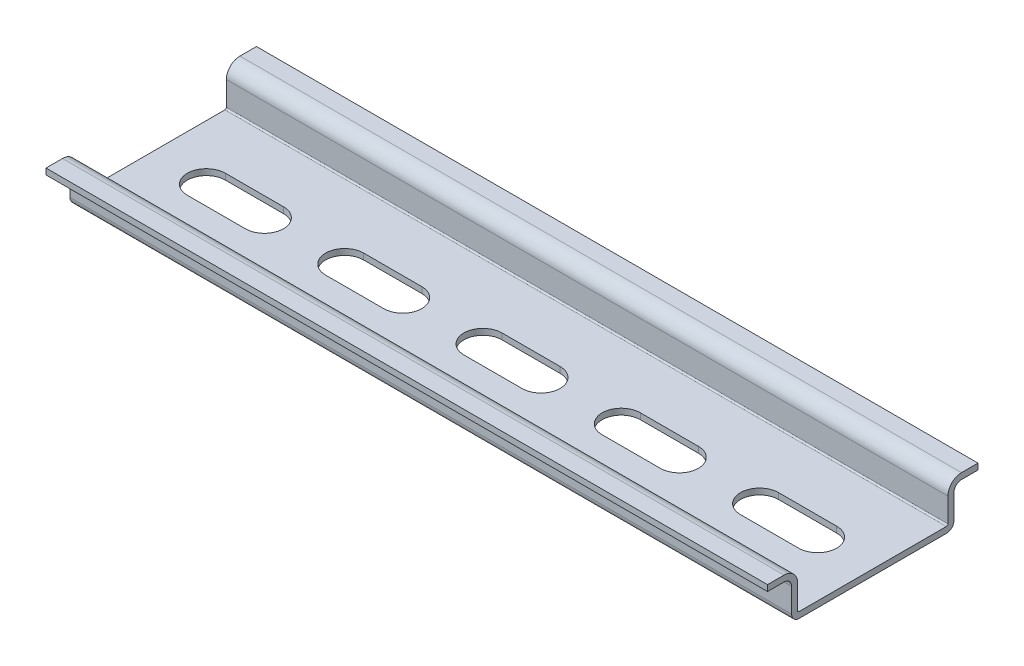
SolidWorks part; units mm, degrees
material "Stainless Steel (ferritic)"
ref_plane "Front Plane" through (0, 0, 0) normal (0, 0, 1) x (1, 0, 0)
ref_plane "Top Plane" through (0, 0, 0) normal (0, 1, 0) x (1, 0, 0)
ref_plane "Right Plane" through (0, 0, 0) normal (1, 0, 0) x (0, 0, -1)
sketch "Sketch1" plane through (0, 0, 0) normal (1, 0, 0) x (0, 0, -1)
  line L12 (12.25, 0) -> (-12.25, 0)
  line L13 (13.5, 1.25) -> (13.5, 5.25)
  line L14 (14.75, 6.5) -> (17.5, 6.5)
  line L15 (-14.75, 6.5) -> (-17.5, 6.5)
  line L16 (-13.5, 1.25) -> (-13.5, 5.25)
  line L17 (14.75, 7.5) -> (17.5, 7.5)
  line L18 (12.5, 1.25) -> (12.5, 5.25)
  line L19 (12.25, 1) -> (-12.25, 1)
  line L20 (-12.5, 1.25) -> (-12.5, 5.25)
  line L21 (-14.75, 7.5) -> (-17.5, 7.5)
  line L22 (17.5, 6.5) -> (17.5, 7.5)
  line L23 (-17.5, 6.5) -> (-17.5, 7.5)
  arc A0 (13.5, 5.25) -> (14.75, 6.5) centre (14.75, 5.25) cw
  arc A1 (-14.75, 6.5) -> (-13.5, 5.25) centre (-14.75, 5.25) cw
  arc A2 (-12.25, 0) -> (-13.5, 1.25) centre (-12.25, 1.25) cw
  arc A3 (12.25, 0) -> (13.5, 1.25) centre (12.25, 1.25) ccw
  arc A4 (12.5, 5.25) -> (14.75, 7.5) centre (14.75, 5.25) cw
  arc A5 (12.25, 1) -> (12.5, 1.25) centre (12.25, 1.25) ccw
  arc A6 (-12.25, 1) -> (-12.5, 1.25) centre (-12.25, 1.25) cw
  arc A7 (-14.75, 7.5) -> (-12.5, 5.25) centre (-14.75, 5.25) cw
  point P0 (0, 0)
  point P17 (0, 0)
  point P45 (0, 0)
  dimension "D12" = 1.25
  dimension "D10" = 35
  dimension "D11" = 27
  dimension "D13" = 7.5
extrude "Boss-Extrude1" add sketch "Sketch1" along normal mid plane 120
sketch "Sketch2" plane through (0, 0, 0) normal (0, -1, 0) x (1, 0, 0)
  line L0 (-60, 0) -> (60, 0) construction
  line L3 (-4.83, 0) -> (4.83, 0) construction
  line L4 (-4.83, 3.17) -> (4.83, 3.17)
  line L5 (-4.83, -3.17) -> (4.83, -3.17)
  line L6 (18.17, -3.17) -> (27.83, -3.17)
  line L7 (18.17, 3.17) -> (27.83, 3.17)
  line L8 (18.17, 0) -> (27.83, 0) construction
  line L9 (-27.83, -3.17) -> (-18.17, -3.17)
  line L10 (-27.83, 3.17) -> (-18.17, 3.17)
  line L11 (-27.83, 0) -> (-18.17, 0) construction
  line L12 (-50.83, 0) -> (-41.17, 0) construction
  line L13 (-50.83, 3.17) -> (-41.17, 3.17)
  line L14 (-50.83, -3.17) -> (-41.17, -3.17)
  line L15 (41.17, 0) -> (50.83, 0) construction
  line L16 (41.17, 3.17) -> (50.83, 3.17)
  line L17 (41.17, -3.17) -> (50.83, -3.17)
  line L18 (-60, 12.25) -> (-60, -12.25) construction
  line L19 (60, 12.25) -> (60, -12.25) construction
  arc A0 (-4.83, 3.17) -> (-4.83, -3.17) centre (-4.83, 0) ccw
  arc A1 (4.83, -3.17) -> (4.83, 3.17) centre (4.83, 0) ccw
  arc A2 (18.17, 3.17) -> (18.17, -3.17) centre (18.17, 0) ccw
  arc A3 (27.83, -3.17) -> (27.83, 3.17) centre (27.83, 0) ccw
  arc A4 (-27.83, 3.17) -> (-27.83, -3.17) centre (-27.83, 0) ccw
  arc A5 (-18.17, -3.17) -> (-18.17, 3.17) centre (-18.17, 0) ccw
  arc A6 (-50.83, 3.17) -> (-50.83, -3.17) centre (-50.83, 0) ccw
  arc A7 (-41.17, -3.17) -> (-41.17, 3.17) centre (-41.17, 0) ccw
  arc A8 (41.17, 3.17) -> (41.17, -3.17) centre (41.17, 0) ccw
  arc A9 (50.83, -3.17) -> (50.83, 3.17) centre (50.83, 0) ccw
  point P2 (0, 0)
  point P3 (-60, 0)
  point P8 (0, 0)
  point P14 (-8, 0)
  point P16 (23, 0)
  point P21 (8, 0)
  point P22 (0, 0)
  point P25 (-46, 0)
  point P27 (15, 0)
  point P28 (31, 0)
  point P31 (-23, 0)
  point P36 (-31, 0)
  point P37 (-15, 0)
  point P39 (0, 0)
  point P45 (46, 0)
  point P50 (0, 0)
  point P51 (0, 0)
  point P52 (60, 0)
  dimension "D1" = 3.17
  dimension "D4" = 3.17
  dimension "D8" = 3.17
  dimension "D3" = 16
  dimension "D2" = 16
  dimension "D5" = 7
  dimension "D6" = 16
  dimension "D7" = 7
  dimension "D9" = 2
  dimension "D10" = 2
extrude "Cut-Extrude1" cut sketch "Sketch2" against normal blind 120
